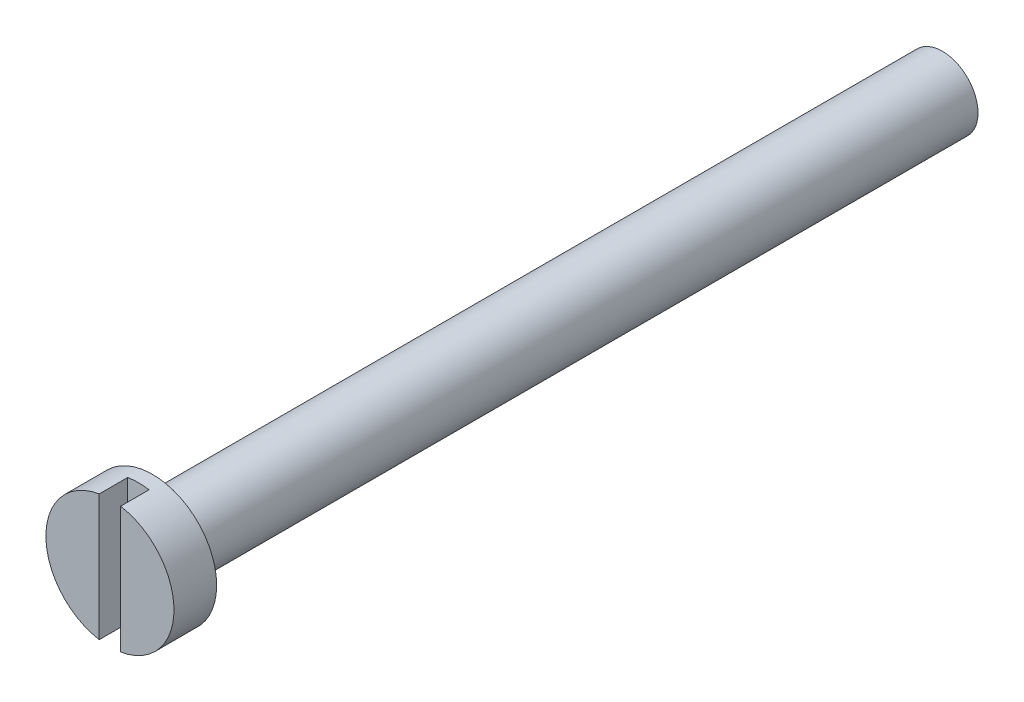
SolidWorks part; units mm, degrees
ref_plane "前视基准面" through (0, 0, 0) normal (0, 0, 1) x (1, 0, 0)
ref_plane "上视基准面" through (0, 0, 0) normal (0, 1, 0) x (1, 0, 0)
ref_plane "右视基准面" through (0, 0, 0) normal (1, 0, 0) x (0, 0, -1)
sketch "草图1" plane through (0, 0, 0) normal (0, 0, 1) x (1, 0, 0)
  circle A0 centre (0, 0) radius 2.5
  dimension "D1" = 5
extrude "凸台-拉伸1" add sketch "草图1" along normal blind 55.5
cosmetic thread "装饰螺纹线2" parameters "D1"=10, "D2"=4.134
sketch "草图2" plane through (0, 0, 55.5) normal (0, 0, 1) x (1, 0, 0)
  circle A0 centre (0, 0) radius 4.5
  dimension "D1" = 9
extrude "凸台-拉伸2" add sketch "草图2" along normal blind 3
sketch "草图4" plane through (0, 0, 58.5) normal (0, 0, 1) x (1, 0, 0)
  line L1 (-0.75, 5.4684) -> (0.75, 5.4684)
  line L2 (-0.75, 5.4684) -> (-0.75, -5.4684)
  line L3 (-0.75, -5.4684) -> (0.75, -5.4684)
  line L4 (0.75, 5.4684) -> (0.75, -5.4684)
  line L5 (-0.75, 5.4684) -> (0.75, -5.4684) construction
  line L6 (-0.75, -5.4684) -> (0.75, 5.4684) construction
  point P0 (0, 0)
  dimension "D1" = 1.5
extrude "切除-拉伸1" cut sketch "草图4" against normal blind 2
sketch "草图5" plane through (0, 0, 0) normal (0, 0, -1) x (-1, 0, 0)
  point P0 (0, 0)
  point P1 (-8.9921, 4.042)
hole_wizard "M3 螺纹孔的螺纹孔钻头1" positions "草图6" profile "草图8" hole size "M3" standard "GB"
sketch "草图6" plane through (0, 0, 0) normal (0, 0, -1) x (-1, 0, 0)
  point P0 (0, 0)
sketch "草图8" plane through (0, 0, 0) normal (1, 0, 0) x (0, 1, 0)
  line L0 (0, 0) -> (0, 10.7511)
  line L1 (0, 10.7511) -> (1.25, 10)
  line L2 (1.25, 10) -> (1.25, 0)
  line L5 (1.25, 0) -> (0, 0)
  line L10 (0, 10.7511) -> (-1.25, 10) construction
  line L11 (0, -6.35) -> (0, 107.95) construction
  dimension "孔直径" = 2.5
  dimension "孔深度" = 10
  dimension "导头角度" = 118
